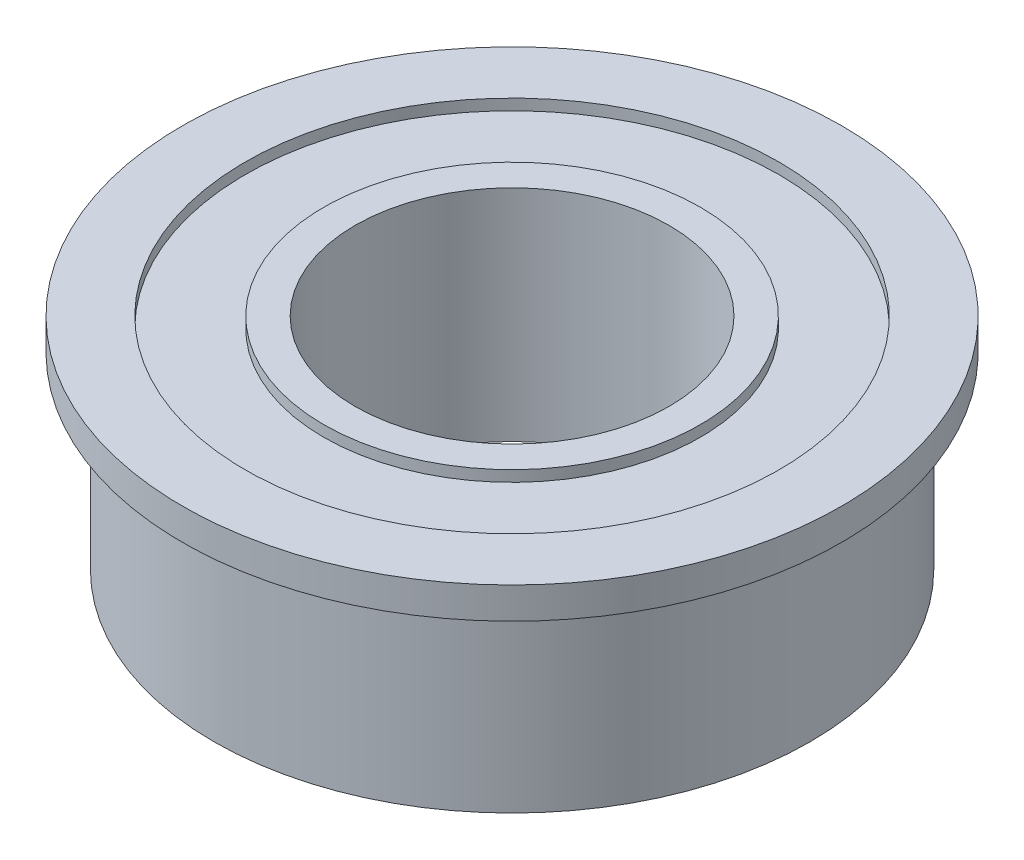
SolidWorks part; units mm, degrees
material "AISI 304"
ref_plane "前视基准面" through (0, 0, 0) normal (0, 0, 1) x (1, 0, 0)
ref_plane "上视基准面" through (0, 0, 0) normal (0, 1, 0) x (1, 0, 0)
ref_plane "右视基准面" through (0, 0, 0) normal (1, 0, 0) x (0, 0, -1)
other "Configuration Table"
sketch "草图2" plane through (0, 0, 0) normal (0, 0, 1) x (1, 0, 0)
  line L0 (0, 0) -> (0, 0.8612) construction
  line L1 (0, 0) -> (1.8966, 0) construction
  line L2 (5, 3.5) -> (5, -3.5)
  line L3 (5, 3.5) -> (6, 3.5)
  line L4 (6, 3.5) -> (6, 3.15)
  line L5 (6, 3.15) -> (8.5, 3.15)
  line L6 (8.5, 3.15) -> (8.5, 3.5)
  line L7 (8.5, 3.5) -> (9.5, 3.5)
  line L8 (9.5, 2.5) -> (9.5, -3.5)
  line L9 (8.5, -3.5) -> (9.5, -3.5)
  line L10 (8.5, -3.15) -> (8.5, -3.5)
  line L11 (6, -3.15) -> (8.5, -3.15)
  line L12 (6, -3.5) -> (6, -3.15)
  line L13 (5, -3.5) -> (6, -3.5)
  line L14 (9.5, 3.5) -> (10.5, 3.5)
  line L15 (10.5, 3.5) -> (10.5, 2.5)
  line L16 (10.5, 2.5) -> (9.5, 2.5)
  point P20 (5, 0)
  dimension "内径" = 10
  dimension "外径" = 19
  dimension "厚度" = 7
  dimension "D1" = 1
  dimension "D2" = 0.35
  dimension "D3" = 21
  dimension "D4" = 1
revolve "旋转1" add sketch "草图2" angle 360 about L0
equation "\"D1@草图2\"=(\"外径@草图2\"-\"内径@草图2\")/9"
equation "\"D2@草图2\"=\"厚度@草图2\"/20"
equation "\"内径\" = 10"
equation "\"外径\" = 19"
equation "\"法兰外径\" = 21"
equation "\"法兰厚度\" = 1"
equation "\"总厚度\"= 7"
equation "\"外径@草图2\"=\"外径\""
equation "\"厚度@草图2\"=\"总厚度\""
equation "\"内径@草图2\"=\"内径\""
equation "\"D3@草图2\"=\"法兰外径\""
equation "\"D4@草图2\"=\"法兰厚度\""
